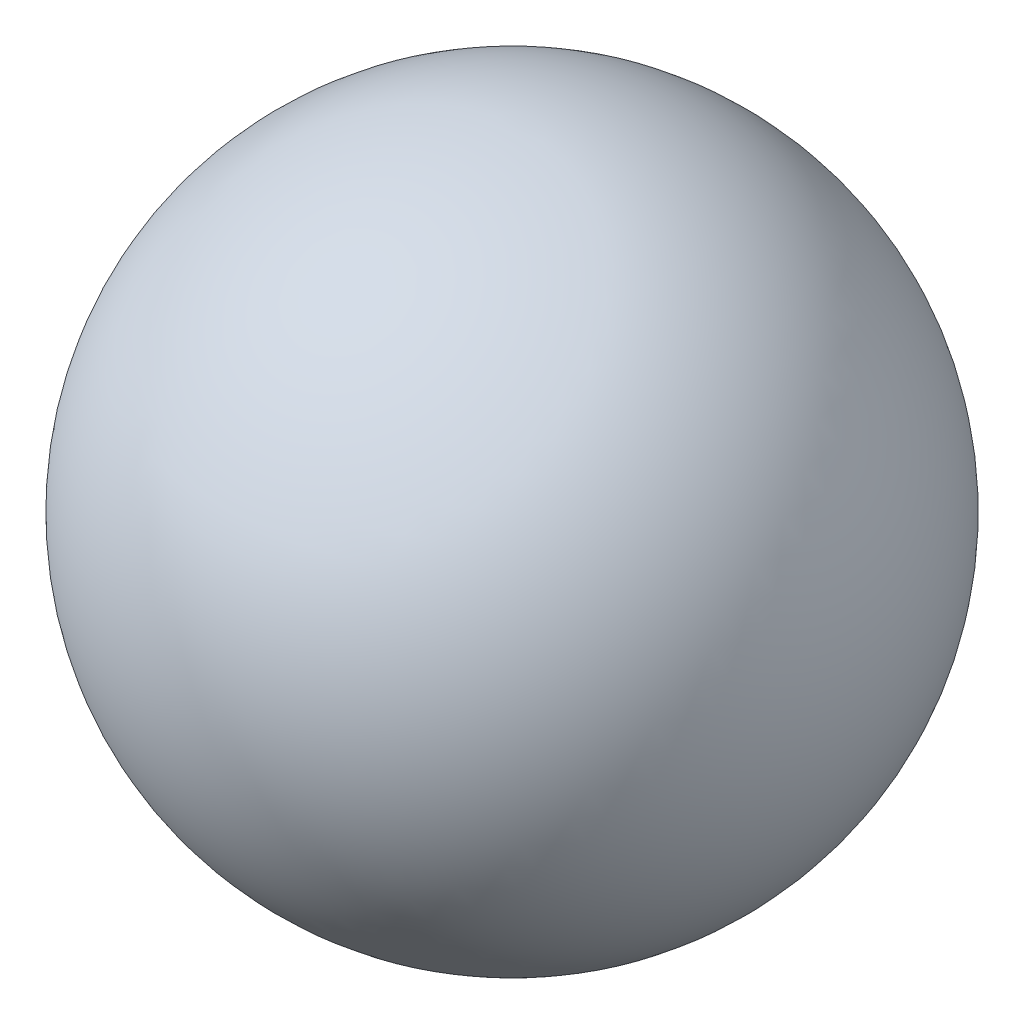
SolidWorks part; units mm, degrees
material "AISI 316 Arkusz stali nierdzewnej (SS)"
ref_plane "Płaszczyzna przednia" through (0, 0, 0) normal (0, 0, 1) x (1, 0, 0)
ref_plane "Płaszczyzna górna" through (0, 0, 0) normal (0, 1, 0) x (1, 0, 0)
ref_plane "Płaszczyzna prawa" through (0, 0, 0) normal (1, 0, 0) x (0, 0, -1)
sketch "Szkic1" plane through (0, 0, 0) normal (0, 0, 1) x (1, 0, 0)
  line L0 (0, 1.6) -> (0, -1.6) construction
  line L1 (0, 1.6) -> (0, -1.6)
  arc A0 (0, 1.6) -> (0, -1.6) centre (0, 0) cw
  circle A1 centre (0, 0) radius 1.6 construction
  point P4 (0, 0)
  dimension "D1" = 1.6
revolve "Obrót1" add sketch "Szkic1" angle 360 about L0
